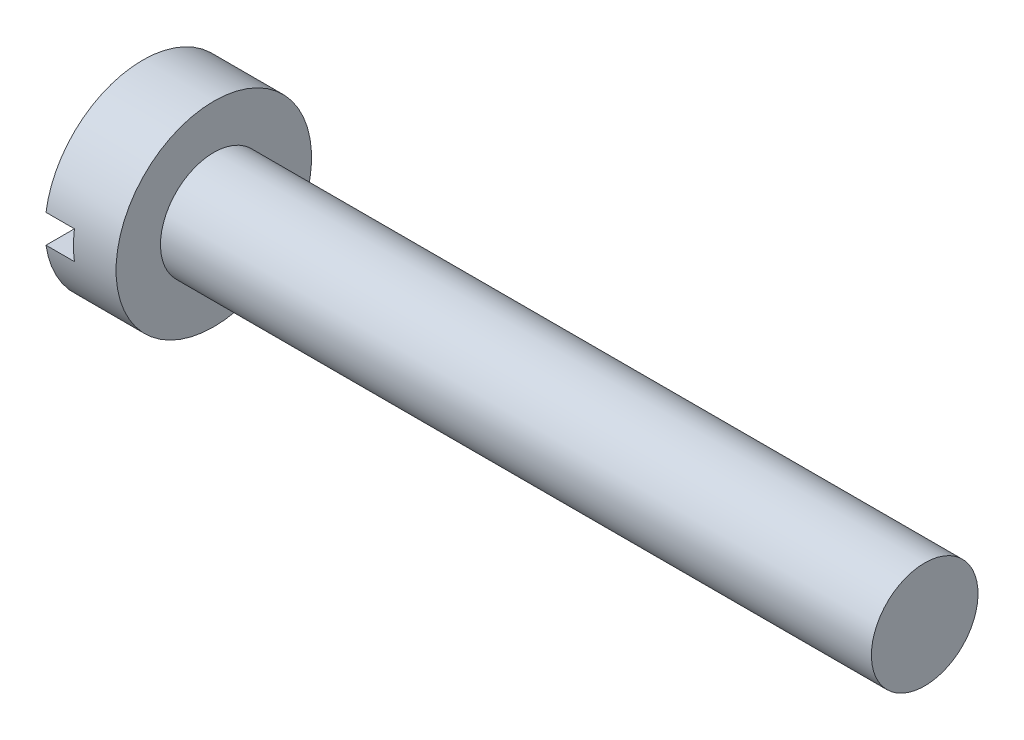
SolidWorks part; units mm, degrees
material "Plain Carbon Steel"
ref_plane "Front Plane" through (0, 0, 0) normal (0, 0, 1) x (1, 0, 0)
ref_plane "Top Plane" through (0, 0, 0) normal (0, 1, 0) x (1, 0, 0)
ref_plane "Right Plane" through (0, 0, 0) normal (1, 0, 0) x (0, 0, -1)
sketch "Sketch1" plane through (0, 0, 0) normal (0, 0, 1) x (1, 0, 0)
  line L0 (0, 0) -> (0, 2.75)
  line L1 (0, 2.75) -> (2, 2.75)
  line L2 (2, 2.75) -> (2, 1.5)
  line L3 (2, 1.5) -> (22, 1.5)
  line L4 (22, 1.5) -> (22, 0)
  line L5 (22, 0) -> (0, 0) construction
  line L6 (0, 0) -> (22, 0)
  dimension "D1" = 3
  dimension "D2" = 20
  dimension "D3" = 5.5
  dimension "D4" = 2
revolve "Revolve1" add sketch "Sketch1" angle 360 about L5
sketch "Sketch2" plane through (0, 0, 0) normal (-1, 0, 0) x (0, 0, 1)
  line L0 (2.75, 0) -> (-2.75, 0) construction
  line L1 (-2.75, 0.4) -> (2.75, 0.4)
  line L2 (-2.75, 0.4) -> (-2.75, -0.4)
  line L3 (-2.75, -0.4) -> (2.75, -0.4)
  line L4 (2.75, 0.4) -> (2.75, -0.4)
  circle A0 centre (0, 0) radius 2.75 construction
  dimension "D1" = 0.8
extrude "Cut-Extrude1" cut sketch "Sketch2" against normal blind 0.8
